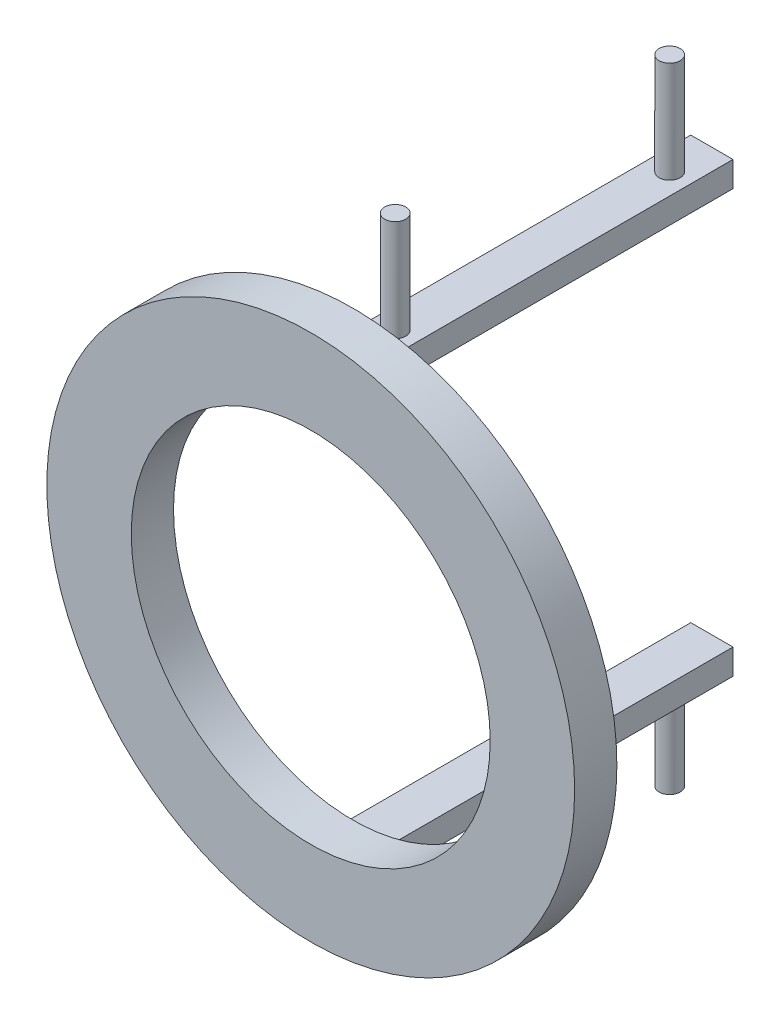
SolidWorks part; units mm, degrees
ref_plane "Front Plane" through (0, 0, 0) normal (0, 0, 1) x (1, 0, 0)
ref_plane "Top Plane" through (0, 0, 0) normal (0, 1, 0) x (1, 0, 0)
ref_plane "Right Plane" through (0, 0, 0) normal (1, 0, 0) x (0, 0, -1)
sketch "Sketch1" plane through (0, 0, 0) normal (0, 0, 1) x (1, 0, 0)
  circle A0 centre (0, 0) radius 12.5
  dimension "D1" = 25
extrude "Boss-Extrude1" add sketch "Sketch1" along normal blind 2
sketch "Sketch2" plane through (0, 0, 2) normal (0, 0, 1) x (1, 0, 0)
  circle A0 centre (0, 0) radius 8.5
  dimension "D1" = 17
extrude "Cut-Extrude1" cut sketch "Sketch2" against normal blind 2
sketch "Sketch5" plane through (0, 0, 0) normal (0, 0, -1) x (-1, 0, 0)
  line L0 (0, 12.5) -> (0, -12.5) construction
  line L1 (-12.5, 0) -> (12.5, 0) construction
  line L2 (-1, -9.4) -> (1, -9.4)
  line L3 (-1, 10.6) -> (1, 10.6)
  line L4 (-1, 10.6) -> (-1, 9.4)
  line L5 (-1, 9.4) -> (1, 9.4)
  line L6 (1, 10.6) -> (1, 9.4)
  line L7 (-1, 10.6) -> (1, 9.4) construction
  line L8 (-1, 9.4) -> (1, 10.6) construction
  line L9 (1, -10.6) -> (1, -9.4)
  line L10 (-1, -10.6) -> (1, -10.6)
  line L11 (-1, -10.6) -> (-1, -9.4)
  circle A0 centre (0, 0) radius 12.5 construction
  point P7 (0, 10)
  point P17 (0, 0)
  dimension "D1" = 2
  dimension "D2" = 1.2
  dimension "D3" = 10
extrude "Boss-Extrude3" add sketch "Sketch5" along normal blind 17
sketch "Sketch7" plane through (0, 0, 0) normal (0, 0, -1) x (-1, 0, 0)
  line L0 (-12.5, 0) -> (12.5, 0) construction
  circle A0 centre (0, 0) radius 12.5 construction
sketch "Sketch8" plane through (0, 10.6, 0) normal (0, 1, 0) x (1, 0, 0)
  line L1 (-1, 0) -> (1, 0) construction
  circle A0 centre (0, 2) radius 0.5
  circle A1 centre (0, 15) radius 0.5
  point P6 (0, 0)
  dimension "D1" = 1
  dimension "D2" = 1
  dimension "D3" = 2
  dimension "D4" = 15
sketch "Sketch9" plane through (0, -10.6, 0) normal (0, -1, 0) x (1, 0, 0)
  line L0 (-12.5, 0) -> (12.5, 0) construction
  line L1 (1, 0) -> (-1, 0) construction
  circle A0 centre (0, -2) radius 0.5
  circle A1 centre (0, -15) radius 0.5
  dimension "D1" = 1
  dimension "D2" = 1
  dimension "D3" = 2
  dimension "D4" = 15
extrude "Boss-Extrude4" add sketch "Sketch8" along normal blind 4.8
extrude "Boss-Extrude5" add sketch "Sketch9" along normal blind 4
